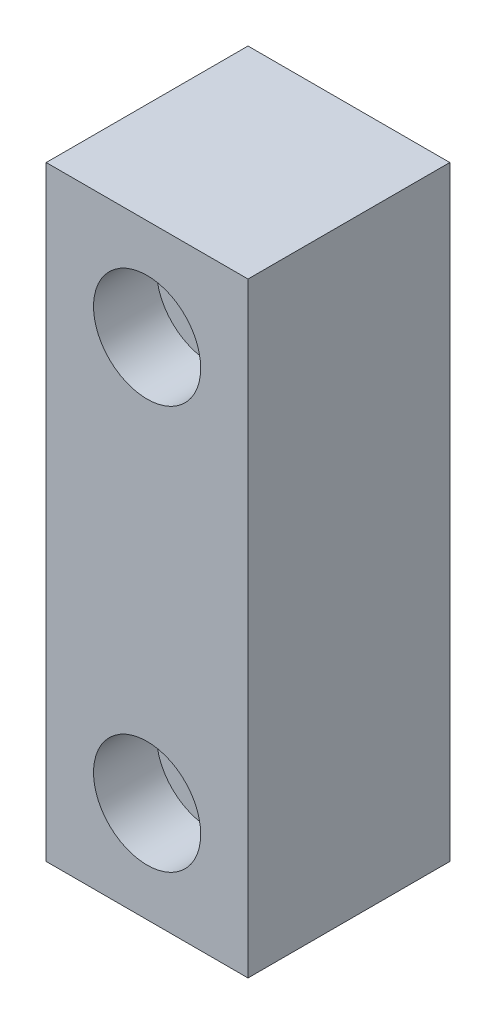
SolidWorks part; units mm, degrees
ref_plane "Front Plane" through (0, 0, 0) normal (1, 0, 0) x (0, 1, 0)
ref_plane "Top Plane" through (0, 0, 0) normal (0, 0, 1) x (0, 1, 0)
ref_plane "Right Plane" through (0, 0, 0) normal (0, 1, 0) x (-1, 0, 0)
sketch "Sketch1" plane through (0, 0, 0) normal (0, 0, 1) x (0, 1, 0)
  line L1 (-38.1, -12.7) -> (38.1, -12.7)
  line L2 (-38.1, -12.7) -> (-38.1, 12.7)
  line L3 (-38.1, 12.7) -> (38.1, 12.7)
  line L4 (38.1, -12.7) -> (38.1, 12.7)
  line L5 (-38.1, -12.7) -> (38.1, 12.7) construction
  line L6 (-38.1, 12.7) -> (38.1, -12.7) construction
  point P0 (0, 0)
extrude "Boss-Extrude1" add sketch "Sketch1" along normal mid plane 25.4
hole_wizard "CBORE for 5/16 Socket Head Cap Screw1" positions "Sketch3" profile "Sketch2" counterbore size "5/16" standard "ANSI Inch"
sketch "Sketch3" plane through (0, 0, 12.7) normal (0, 0, 1) x (1, 0, 0)
  point P0 (0, -25.4)
sketch "Sketch2" plane through (0, -25.4, 12.7) normal (1, 0, 0) x (0, -1, 0)
  line L0 (0, 0) -> (0, 28.025)
  line L1 (0, 28.025) -> (4.3688, 25.4)
  line L2 (4.3688, 25.4) -> (4.3688, 7.9248)
  line L3 (4.3688, 7.9248) -> (6.7437, 7.9248)
  line L4 (6.7437, 7.9248) -> (6.7437, 0)
  line L5 (6.7437, 0) -> (0, 0)
  line L10 (0, 28.025) -> (-4.3688, 25.4) construction
  line L11 (0, -6.35) -> (0, 107.95) construction
  dimension "Hole Dia." = 8.7376
  dimension "Hole Depth" = 25.4
  dimension "C'Bore Dia." = 13.4874
  dimension "C'Bore Depth" = 7.9248
  dimension "Drill Angle" = 118
hole_wizard "CBORE for 5/16 Socket Head Cap Screw2" positions "Sketch5" profile "Sketch4" counterbore size "5/16" standard "ANSI Inch"
sketch "Sketch5" plane through (0, 0, 12.7) normal (0, 0, 1) x (1, 0, 0)
  point P0 (0, 25.4)
sketch "Sketch4" plane through (0, 25.4, 12.7) normal (1, 0, 0) x (0, -1, 0)
  line L0 (0, 0) -> (0, 28.025)
  line L1 (0, 28.025) -> (4.3688, 25.4)
  line L2 (4.3688, 25.4) -> (4.3688, 7.9248)
  line L3 (4.3688, 7.9248) -> (6.7437, 7.9248)
  line L4 (6.7437, 7.9248) -> (6.7437, 0)
  line L5 (6.7437, 0) -> (0, 0)
  line L10 (0, 28.025) -> (-4.3688, 25.4) construction
  line L11 (0, -6.35) -> (0, 107.95) construction
  dimension "Hole Dia." = 8.7376
  dimension "Hole Depth" = 25.4
  dimension "C'Bore Dia." = 13.4874
  dimension "C'Bore Depth" = 7.9248
  dimension "Drill Angle" = 118
